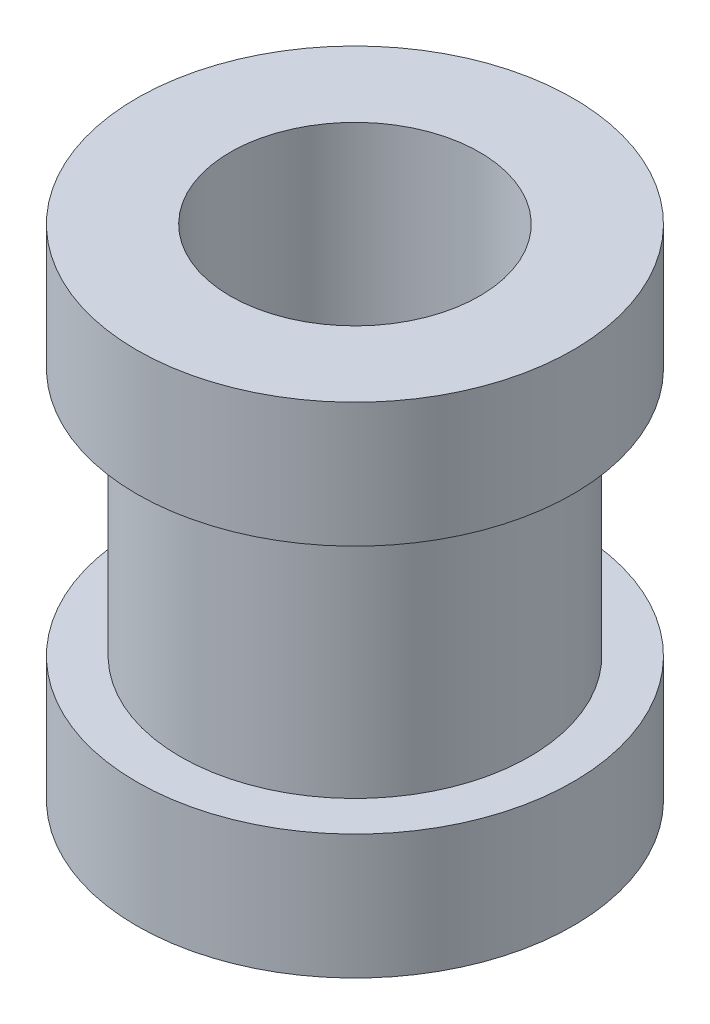
SolidWorks part; units mm, degrees
ref_plane "Front Plane" through (0, 0, 0) normal (0, 0, 1) x (1, 0, 0)
ref_plane "Top Plane" through (0, 0, 0) normal (0, 1, 0) x (1, 0, 0)
ref_plane "Right Plane" through (0, 0, 0) normal (1, 0, 0) x (0, 0, -1)
sketch "Sketch1" plane through (0, 0, 0) normal (0, 1, 0) x (1, 0, 0)
  circle A0 centre (0, 0) radius 1.4
  dimension "D1" = 2.8
extrude "Boss-Extrude1" add sketch "Sketch1" along normal mid plane 4
sketch "Sketch2" plane through (0, 2, 0) normal (0, 1, 0) x (1, 0, 0)
  circle A0 centre (0, 0) radius 1.75
  dimension "D1" = 3.5
extrude "Boss-Extrude2" add sketch "Sketch2" against normal blind 1
mirror "Mirror1" about plane through (0, 0, 0) normal (0, 1, 0) of "Boss-Extrude2"
sketch "Sketch3" plane through (0, 0, 0) normal (0, 1, 0) x (1, 0, 0)
  circle A0 centre (0, 0) radius 1
  dimension "D1" = 2
extrude "Cut-Extrude1" cut sketch "Sketch3" against normal through all both and the other way through all
